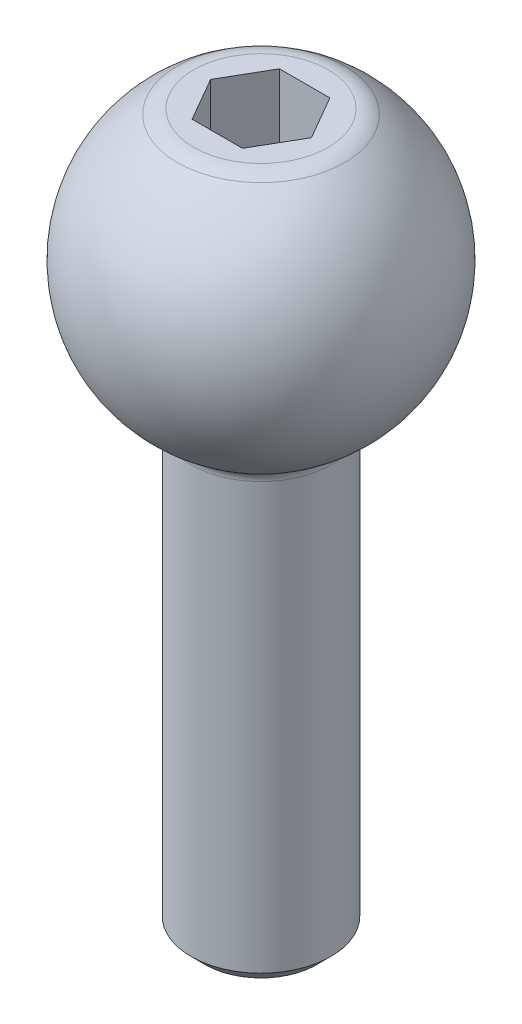
SolidWorks part; units mm, degrees
material "Alloy Steel"
ref_plane "Front Plane" through (0, 0, 0) normal (0, 0, 1) x (1, 0, 0)
ref_plane "Top Plane" through (0, 0, 0) normal (0, 1, 0) x (1, 0, 0)
ref_plane "Right Plane" through (0, 0, 0) normal (1, 0, 0) x (0, 0, -1)
sketch "Sketch1" plane through (0, 0, 0) normal (0, 0, 1) x (1, 0, 0)
  line L0 (0, -107.8367) -> (0, 5283.9963) construction
  line L1 (-1.905, -3.6616) -> (-1.905, -15.875)
  line L2 (-1.905, -15.875) -> (0, -15.875)
  arc A0 (0, 4.1275) -> (0, -4.1275) centre (0, 0) ccw
  dimension "D1" = 4.1275
  dimension "D2" = 15.875
  dimension "D3" = 3.81
revolve "Revolve1" add sketch "Sketch1" angle 360 about L0
fillet "Fillet1" radius 0.381 1 edges at (1.905, -3.6616, 0)
cosmetic thread "Cosmetic Thread1" parameters "D2"=2.7483
chamfer "Chamfer1" distance 0.381 angle 45 1 edges at (1.905, -15.875, 0)
sketch "Sketch2" plane through (0, 0, 0) normal (0, 0, 1) x (1, 0, 0)
  line L0 (1.905, -15.494) -> (1.524, -15.875)
  line L1 (-1.524, -15.875) -> (-1.905, -15.494)
  line L2 (-1.524, -15.875) -> (1.524, -15.875)
  line L3 (-1.905, -3.886) -> (-1.905, -15.494)
  line L4 (1.905, -15.494) -> (1.905, -3.886)
  line L5 (1.905, -15.494) -> (1.905, -3.886) construction
  line L6 (-1.905, -3.886) -> (-1.905, -15.494) construction
  line L7 (-1.524, -15.875) -> (1.524, -15.875) construction
  line L8 (-1.524, -15.875) -> (-1.905, -15.494) construction
  line L9 (1.905, -15.494) -> (1.524, -15.875) construction
  line L10 (-2.0638, 3.5745) -> (2.0638, 3.5745)
  arc A0 (2.0928, -3.5576) -> (1.905, -3.886) centre (2.286, -3.886) ccw
  arc A1 (-1.905, -3.886) -> (-2.0928, -3.5576) centre (-2.286, -3.886) ccw
  arc A2 (2.0928, -3.5576) -> (-2.0928, -3.5576) centre (0, 0) ccw
  arc A3 (2.0928, -3.5576) -> (-2.0928, -3.5576) centre (0, 0) ccw construction
  arc A4 (-1.905, -3.886) -> (-2.0928, -3.5576) centre (-2.286, -3.886) ccw construction
  arc A5 (2.0928, -3.5576) -> (1.905, -3.886) centre (2.286, -3.886) ccw construction
  dimension "D1" = 4.1275
ref_plane "Plane1" through (0, 3.5745, 0) normal (0, 1, 0) x (1, 0, 0)
split "Split1" trim tools "Plane1" bodies to split 101 resulting bodies 104
fillet "Fillet2" radius 0.8128 1 edges at (0, 3.5745, 2.0637)
sketch "Sketch4" plane through (0, 3.5745, 0) normal (0, 1, 0) x (1, 0, 0)
  line L1 (0.6874, -1.1906) -> (1.3748, 0)
  line L2 (1.3748, 0) -> (0.6874, 1.1906)
  line L3 (0.6874, 1.1906) -> (-0.6874, 1.1906)
  line L4 (-0.6874, 1.1906) -> (-1.3748, 0)
  line L5 (-1.3748, 0) -> (-0.6874, -1.1906)
  line L6 (-0.6874, -1.1906) -> (0.6874, -1.1906)
  circle A0 centre (0, 0) radius 1.1906 construction
  dimension "D1" = 2.3813
extrude "Cut-Extrude1" cut sketch "Sketch4" against normal blind 2.54
